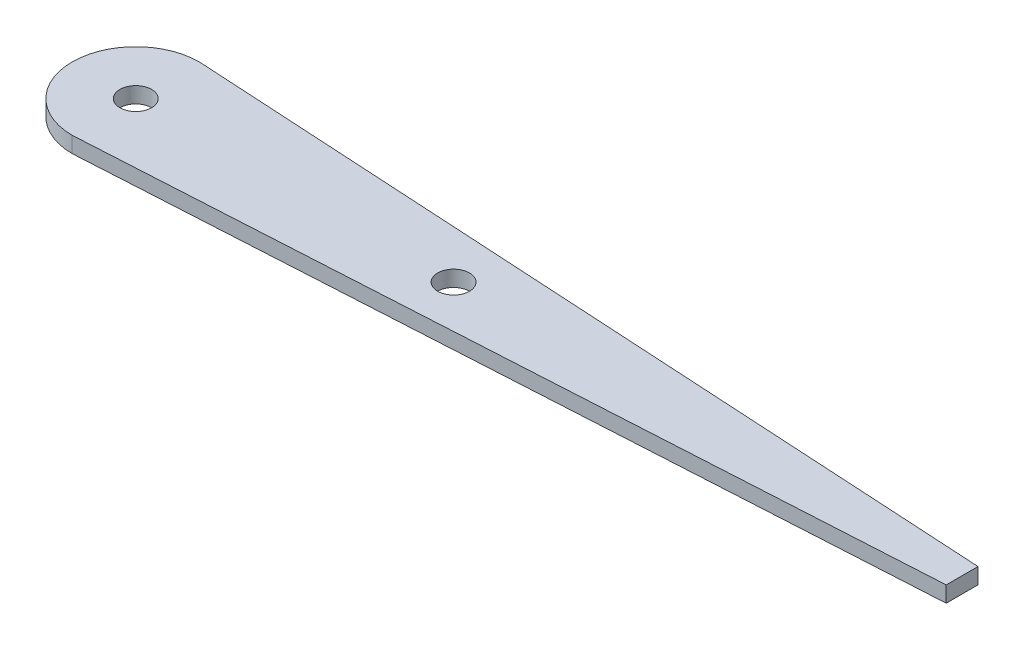
SolidWorks part; units mm, degrees
material "6061-T4 (SS)"
ref_plane "Front Plane" through (0, 0, 0) normal (0, 0, 1) x (1, 0, 0)
ref_plane "Top Plane" through (0, 0, 0) normal (0, 1, 0) x (1, 0, 0)
ref_plane "Right Plane" through (0, 0, 0) normal (1, 0, 0) x (0, 0, -1)
sketch "Sketch2" plane through (0, 0, 0) normal (0, 1, 0) x (1, 0, 0)
  line L0 (8.8914, 0) -> (-8.8914, 0) construction
  line L1 (-31.75, -6.35) -> (50.8, -1.5875)
  line L2 (50.8, -1.5875) -> (50.8, 1.5875)
  line L3 (-31.75, 6.35) -> (50.8, 1.5875)
  circle A0 centre (0, 0) radius 1.5875
  circle A1 centre (-31.75, 0) radius 1.5875
  arc A2 (-31.75, -6.35) -> (-31.75, 6.35) centre (-31.75, 0) cw
  point P7 (-38.1, 0)
  point P15 (50.8, -1.5875)
  point P22 (50.8, 0)
  dimension "D1" = 3.175
  dimension "D2" = 3.175
  dimension "D3" = 6.35
  dimension "D4" = 38.1
  dimension "D5" = 3.175
  dimension "D6" = 88.9
extrude "Boss-Extrude1" add sketch "Sketch2" along normal blind 1.5875
